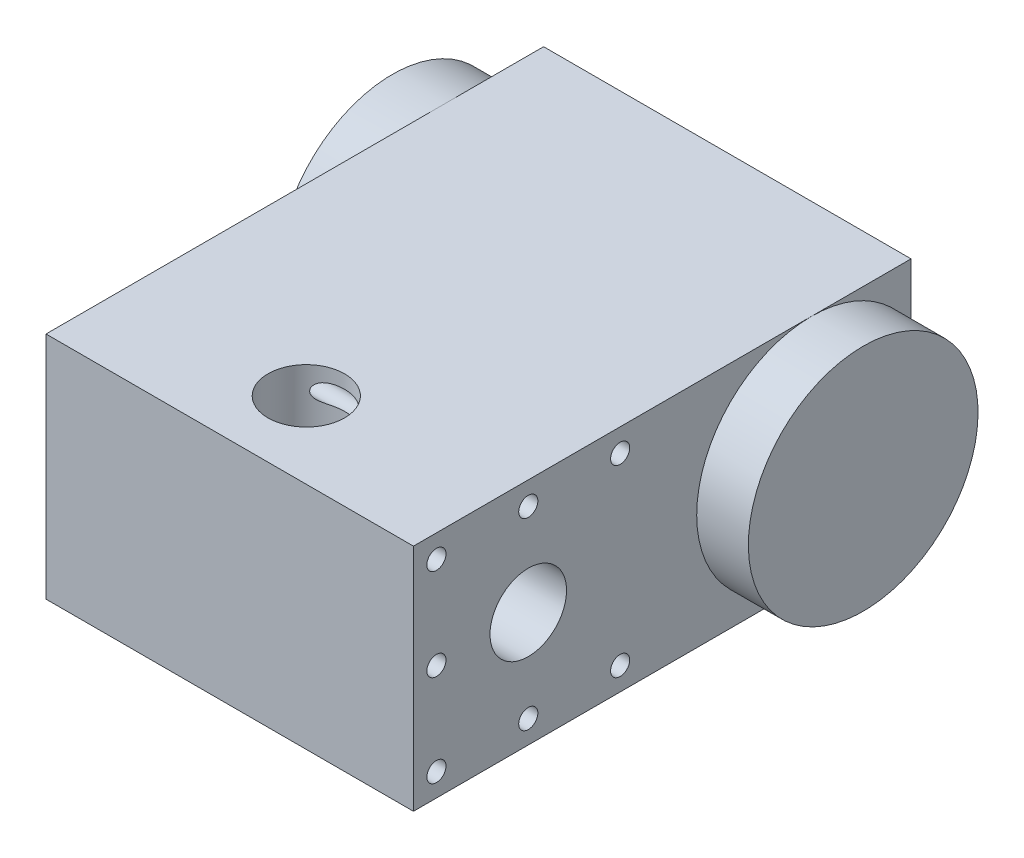
SolidWorks part; units mm, degrees
ref_plane "前视基准面" through (0, 0, 0) normal (0, 0, 1) x (1, 0, 0)
ref_plane "上视基准面" through (0, 0, 0) normal (0, 1, 0) x (1, 0, 0)
ref_plane "右视基准面" through (0, 0, 0) normal (1, 0, 0) x (0, 0, -1)
sketch "草图1" plane through (0, 0, 0) normal (0, 0, 1) x (1, 0, 0)
  line L1 (24, 15) -> (-24, 15)
  line L2 (24, 15) -> (24, -15)
  line L3 (24, -15) -> (-24, -15)
  line L4 (-24, 15) -> (-24, -15)
  line L5 (24, 15) -> (-24, -15) construction
  line L6 (24, -15) -> (-24, 15) construction
  point P0 (0, 0)
  dimension "D1" = 48
  dimension "D2" = 30
extrude "凸台-拉伸1" add sketch "草图1" along normal blind 65
sketch "草图2" plane through (-24, 0, 0) normal (-1, 0, 0) x (0, 0, 1)
  circle A0 centre (13, 0) radius 15
  dimension "D1" = 30
  dimension "D2" = 13
extrude "凸台-拉伸2" add sketch "草图2" along normal blind 6.75
sketch "草图3" plane through (24, 0, 0) normal (1, 0, 0) x (0, 0, -1)
  line L0 (0, -15) -> (0, 15) construction
  circle A0 centre (-13, 0) radius 15
  dimension "D1" = 30
  dimension "D2" = 13
extrude "凸台-拉伸3" add sketch "草图3" along normal blind 6.75
sketch "草图4" plane through (24, 0, 0) normal (1, 0, 0) x (0, 0, -1)
  line L0 (-65, -15) -> (-65, 15) construction
  line L1 (-62, 12) -> (-38, 12) construction
  line L2 (-62, 12) -> (-62, -12) construction
  line L3 (-62, -12) -> (-38, -12) construction
  line L4 (-38, 12) -> (-38, -12) construction
  line L5 (-62, 12) -> (-38, -12) construction
  line L6 (-62, -12) -> (-38, 12) construction
  line L7 (-65, 15) -> (-13, 15) construction
  circle A0 centre (-62, 12) radius 1.25
  circle A1 centre (-38, 12) radius 1.25
  circle A2 centre (-38, -12) radius 1.25
  circle A3 centre (-62, -12) radius 1.25
  circle A4 centre (-50, 12) radius 1.25
  circle A5 centre (-50, -12) radius 1.25
  circle A6 centre (-62, 0) radius 1.25
  circle A7 centre (-50, 0) radius 5
  point P0 (-50, 0)
  dimension "D5" = 2.5
  dimension "D6" = 2.5
  dimension "D7" = 2.5
  dimension "D8" = 2.5
  dimension "D9" = 2.5
  dimension "D10" = 2.5
  dimension "D11" = 2.5
  dimension "D12" = 10
  dimension "D1" = 24
  dimension "D2" = 24
  dimension "D3" = 3
  dimension "D4" = 3
extrude "切除-拉伸1" cut sketch "草图4" against normal through all
sketch "草图5" plane through (0, -15, 0) normal (0, -1, 0) x (1, 0, 0)
  line L0 (-24, 65) -> (24, 65) construction
  circle A0 centre (0, 55) radius 5
  dimension "D1" = 10
  dimension "D2" = 10
extrude "切除-拉伸2" cut sketch "草图5" against normal blind 33
sketch "草图6" plane through (0, 0, 65) normal (0, 0, 1) x (1, 0, 0)
  circle A0 centre (0, 0) radius 5
  dimension "D1" = 10
extrude "凸台-拉伸4" add sketch "草图6" against normal blind 10
